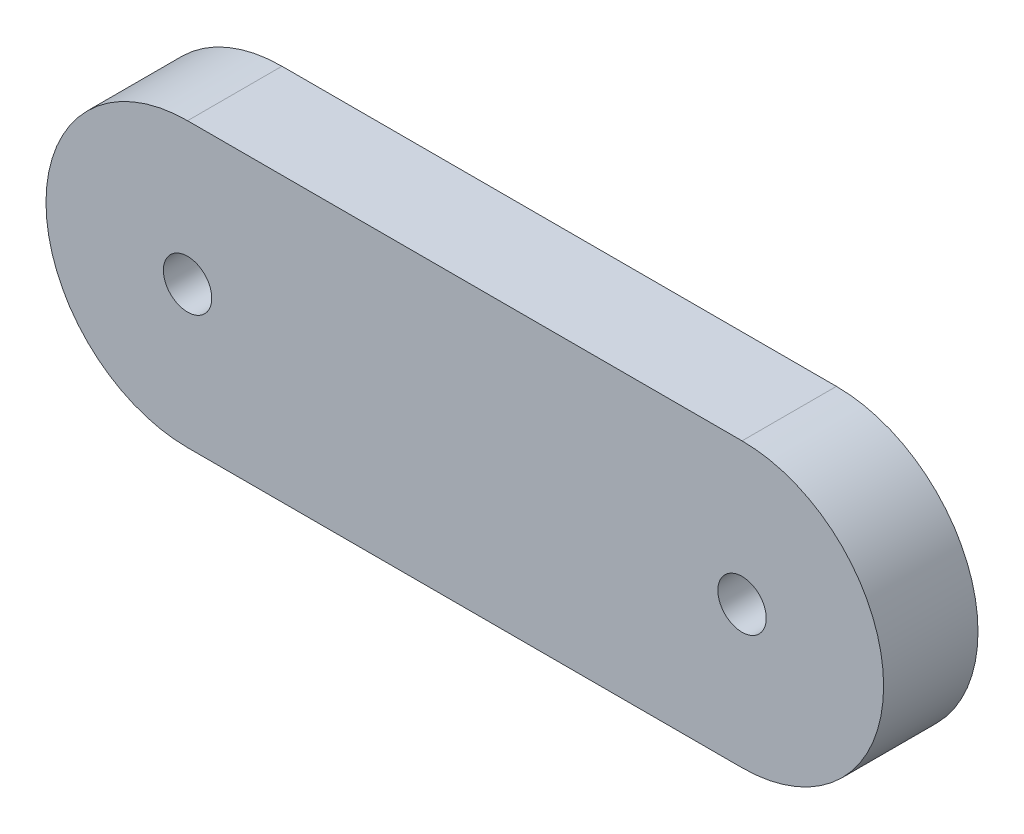
SolidWorks part; units mm, degrees
ref_plane "Front Plane" through (0, 0, 0) normal (0, 0, 1) x (1, 0, 0)
ref_plane "Top Plane" through (0, 0, 0) normal (0, 1, 0) x (1, 0, 0)
ref_plane "Right Plane" through (0, 0, 0) normal (1, 0, 0) x (0, 0, -1)
sketch "Sketch1" plane through (0, 0, 0) normal (0, 0, 1) x (1, 0, 0)
  line L0 (-11.8178, 0.4435) -> (11.6822, 0.4435) construction
  line L1 (-11.8178, 6.4435) -> (11.6822, 6.4435)
  line L2 (-11.8178, -5.5565) -> (11.6822, -5.5565)
  arc A0 (-11.8178, 6.4435) -> (-11.8178, -5.5565) centre (-11.8178, 0.4435) ccw
  arc A1 (11.6822, -5.5565) -> (11.6822, 6.4435) centre (11.6822, 0.4435) ccw
  point P2 (-0.0678, 0.4435)
  dimension "D2" = 6
  dimension "D1" = 23.5
extrude "Boss-Extrude1" add sketch "Sketch1" along normal mid plane 4
hole_wizard "Tap Drill for M2.5x0.45 Tap1" positions "3DSketch2" profile "Sketch4" hole size "M2.5x0.45" standard "ANSI Metric" end condition through all
sketch3d "3DSketch2"
  line L0 (-11.8178, 0.4435, 2) -> (-11.8178, 0.4435, -2) construction
  line L1 (11.6822, 0.4435, 2) -> (11.6822, 0.4435, -2) construction
  point P0 (-11.8178, 0.4435, 2)
  point P4 (11.6822, 0.4435, 2)
sketch "Sketch4" plane through (-11.8178, 0.4435, 2) normal (1, 0, 0) x (0, -1, 0)
  line L0 (0, 0) -> (0, 4)
  line L1 (0, 4) -> (1.025, 4)
  line L2 (1.025, 4) -> (1.025, 0)
  line L5 (1.025, 0) -> (0, 0)
  line L11 (0, -6.35) -> (0, 107.95) construction
  dimension "Thru Hole Dia." = 2.05
  dimension "Thru Hole Depth" = 4
